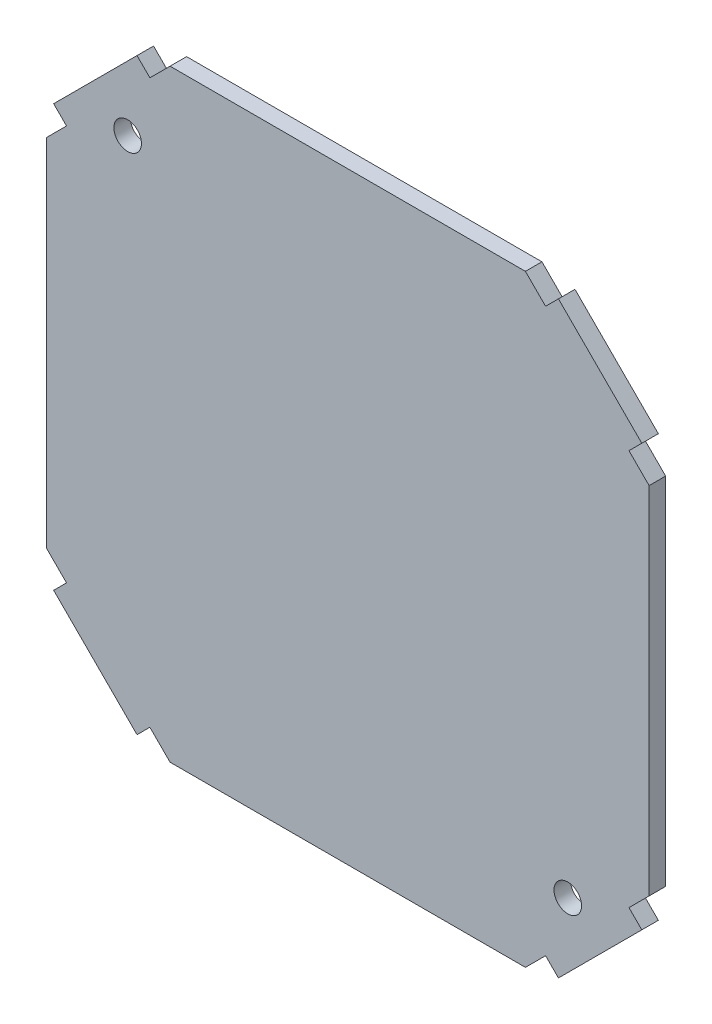
SolidWorks part; units mm, degrees
ref_plane "Plan de face" through (0, 0, 0) normal (0, 0, 1) x (1, 0, 0)
ref_plane "Plan de dessus" through (0, 0, 0) normal (0, 1, 0) x (1, 0, 0)
ref_plane "Plan de droite" through (0, 0, 0) normal (1, 0, 0) x (0, 0, -1)
sketch "Esquisse1" plane through (0, 0, 3) normal (0, 0, 1) x (1, 0, 0)
  line L0 (29.807, 53.9722) -> (29.807, -55.4278) construction
  line L1 (-24.893, -0.7278) -> (84.507, -0.7278) construction
  line L2 (68.0486, 52.6459) -> (83.1807, 37.5138)
  line L3 (83.1807, 37.5138) -> (80.8472, 35.1804)
  line L4 (65.7151, 50.3124) -> (68.0486, 52.6459)
  line L5 (83.1807, -38.9693) -> (68.0486, -54.1014)
  line L6 (68.0486, -54.1014) -> (65.7151, -51.768)
  line L7 (80.8472, -36.6359) -> (83.1807, -38.9693)
  line L8 (-8.4345, -54.1014) -> (-23.5666, -38.9693)
  line L9 (-23.5666, -38.9693) -> (-21.2332, -36.6359)
  line L10 (-6.1011, -51.768) -> (-8.4345, -54.1014)
  line L11 (-13.6671, 42.7464) -> (73.2812, -44.2019) construction
  line L12 (-13.6671, -44.2019) -> (73.2812, 42.7464) construction
  line L17 (-21.2332, 35.1804) -> (-23.5666, 37.5138)
  line L18 (-8.2224, 52.858) -> (-23.7788, 37.3017) construction
  line L19 (-23.5666, 37.5138) -> (-8.4345, 52.6459)
  line L20 (-8.4345, 52.6459) -> (-6.1011, 50.3124)
  line L22 (-23.7788, 37.3017) -> (-21.6574, 35.1804) construction
  line L23 (-6.1011, 50.7367) -> (-8.2224, 52.858) construction
  line L25 (-24.893, -32.9761) -> (-2.4413, -55.4278)
  line L26 (-2.4413, -55.4278) -> (62.0553, -55.4278)
  line L27 (62.0553, -55.4278) -> (84.507, -32.9761)
  line L28 (84.507, -32.9761) -> (84.507, 31.5206)
  line L29 (84.507, 31.5206) -> (62.0553, 53.9722)
  line L30 (62.0553, 53.9722) -> (-2.4413, 53.9722)
  line L31 (-2.4413, 53.9722) -> (-24.893, 31.5206)
  line L32 (-24.893, 31.5206) -> (-24.893, -32.9761)
  line L33 (-24.893, -32.9761) -> (-2.4413, -55.4278)
  line L34 (-2.4413, -55.4278) -> (62.0553, -55.4278)
  line L35 (62.0553, -55.4278) -> (84.507, -32.9761)
  line L36 (84.507, -32.9761) -> (84.507, 31.5206)
  line L37 (84.507, 31.5206) -> (62.0553, 53.9722)
  line L38 (62.0553, 53.9722) -> (-2.4413, 53.9722)
  line L39 (-2.4413, 53.9722) -> (-24.893, 31.5206)
  line L40 (-24.893, 31.5206) -> (-24.893, -32.9761)
  circle A0 centre (-10.1316, 39.2109) radius 2.5
  circle A1 centre (69.7456, -40.6664) radius 2.5
  point P19 (29.807, -0.7278)
  point P38 (29.807, -0.7278)
  dimension "D5" = 5
  dimension "D2" = 0.3
  dimension "D3" = 0.3
  dimension "D4" = 4
  dimension "D6" = 5
  dimension "D1" = 0.3
extrude "Boss.-Extru.1" add sketch "Esquisse1" along a picked direction on the side against the normal blind 3 contours L39 L40 L33 L34 L35 L36 L37 L38 | L37 L3 L2 L4 | L39 L20 L19 L17 | L33 L9 L8 L10 | L35 L6 L5 L7
